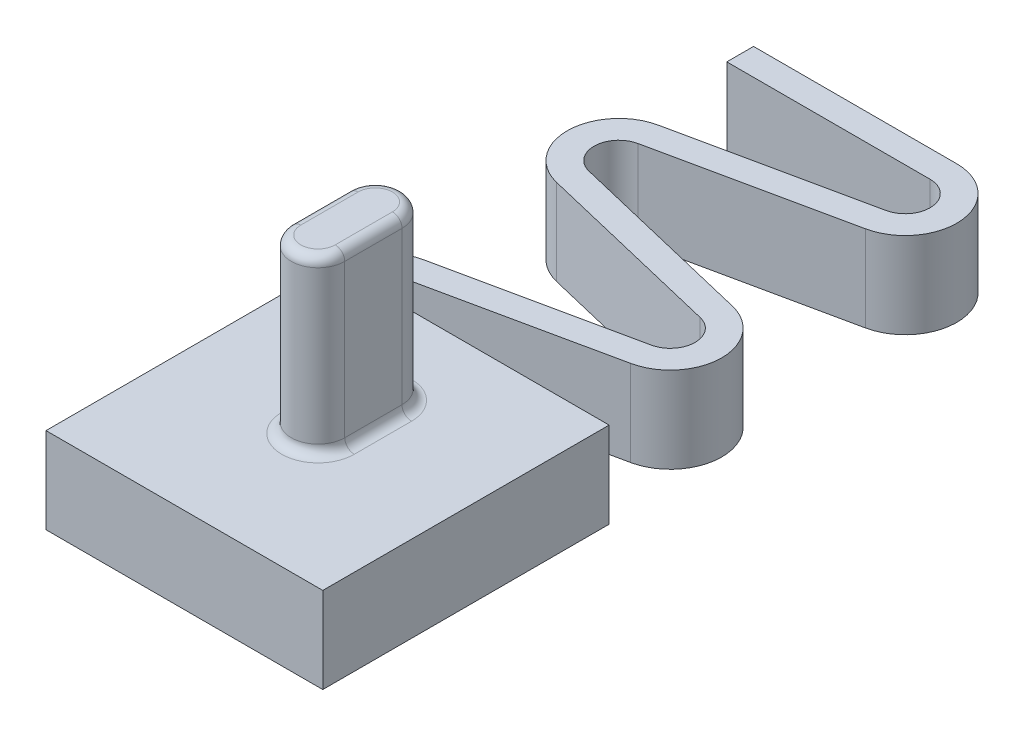
SolidWorks part; units mm, degrees
ref_plane "Front Plane" through (0, 0, 0) normal (0, 0, 1) x (1, 0, 0)
ref_plane "Top Plane" through (0, 0, 0) normal (0, 1, 0) x (1, 0, 0)
ref_plane "Right Plane" through (0, 0, 0) normal (1, 0, 0) x (0, 0, -1)
sketch "Sketch1" plane through (0, 0, 0) normal (0, 1, 0) x (1, 0, 0)
  line L1 (7.25, 7.5) -> (-7.25, 7.5)
  line L2 (7.25, 7.5) -> (7.25, -7.5)
  line L3 (7.25, -7.5) -> (-7.25, -7.5)
  line L4 (-7.25, 7.5) -> (-7.25, -7.5)
  line L5 (7.25, 7.5) -> (-7.25, -7.5) construction
  line L6 (7.25, -7.5) -> (-7.25, 7.5) construction
  point P0 (0, 0)
  dimension "D1" = 14.5
  dimension "D2" = 15
extrude "Boss-Extrude1" add sketch "Sketch1" along normal blind 4.5 contours L1 L4 L3 L2
sketch "Sketch2" plane through (0, 4.5, 0) normal (0, 1, 0) x (1, 0, 0)
  line L0 (0, 0) -> (0, 50000) construction
  line L1 (7.25, -7.5) -> (-7.25, -7.5) construction
  line L2 (7.5, 27.5) -> (-7.5, 27.5) construction
  line L3 (7.5, 27.5) -> (7.5, -7.5) construction
  line L4 (7.5, -7.5) -> (-7.5, -7.5) construction
  line L5 (-7.5, 27.5) -> (-7.5, -7.5) construction
  line L6 (7.5, 27.5) -> (-7.5, -7.5) construction
  line L7 (7.5, -7.5) -> (-7.5, 27.5) construction
  line L8 (7.25, 7.5) -> (-7.25, 7.5) construction
  line L10 (-4.9658, 9.4563) -> (4.8658, 11.5461)
  line L11 (4.9158, 15.4474) -> (-4.9658, 17.814)
  line L12 (-6.55, 7.5) -> (-6.55, 5.5405)
  line L14 (-7.25, 7.5) -> (-7.25, -7.5) construction
  line L15 (-4.9158, 21.7153) -> (4.9158, 23.8051)
  line L16 (4.5, 27.7614) -> (-6.1466, 27.7614)
  arc A0 (-6.55, 7.5) -> (-4.9658, 9.4563) centre (-4.55, 7.5) cw
  arc A1 (4.9158, 15.4474) -> (4.8658, 11.5461) centre (4.45, 13.5024) cw
  arc A2 (-4.9658, 17.814) -> (-4.9158, 21.7153) centre (-4.5, 19.759) cw
  arc A3 (4.9158, 23.8051) -> (4.5, 27.7614) centre (4.5, 25.7614) ccw
  point P3 (0, 10)
  point P28 (3.9022, 26.8984)
  point P29 (-6.1898, 26.98)
  point P30 (0, 0)
  point P31 (0, 0)
  point P32 (0, 0)
  dimension "D4" = 2
  dimension "D5" = 2
  dimension "D6" = 2
  dimension "D7" = 2
  dimension "D1" = 15
  dimension "D2" = 35
  dimension "D3" = 0.7
  dimension "D8" = 12
  dimension "D9" = 3
  dimension "D10" = 3
extrude "Extrude-Thin1" add sketch "Sketch2" against normal up to surface (4.5 mm away) thin up to face at (0, 0, 0) thin type mid plane wall 1.4
sketch "Sketch3" plane through (0, 4.5, 0) normal (0, 1, 0) x (1, 0, 0)
  line L0 (0, 0) -> (0, -50000) construction
  line L1 (0, 2.5) -> (0, -0.5) construction
  line L2 (1.4, 2.5) -> (1.4, -0.5)
  line L3 (-1.4, 2.5) -> (-1.4, -0.5)
  line L4 (7.25, -7.5) -> (-7.25, -7.5) construction
  arc A0 (1.4, 2.5) -> (-1.4, 2.5) centre (0, 2.5) ccw
  arc A1 (-1.4, -0.5) -> (1.4, -0.5) centre (0, -0.5) ccw
  point P5 (0, 1)
  point P10 (0, 0)
  point P11 (-0.3031, -2.6403)
  point P12 (3.0247, -1.4244)
  point P13 (0.2976, -2.0772)
  point P15 (0, 1.5089)
  dimension "D1" = 1.4
  dimension "D2" = 3
  dimension "D3" = 7
extrude "Boss-Extrude2" add sketch "Sketch3" along normal blind 9
fillet "Fillet2" radius 0.5 8 edges at (0, 13.5, 1.9) (-1.4, 13.5, -1) (0, 13.5, -3.9) (0, 4.5, 1.9) (-1.4, 4.5, -1) (0, 4.5, -3.9) (1.4, 13.5, -1) (1.4, 4.5, -1)
